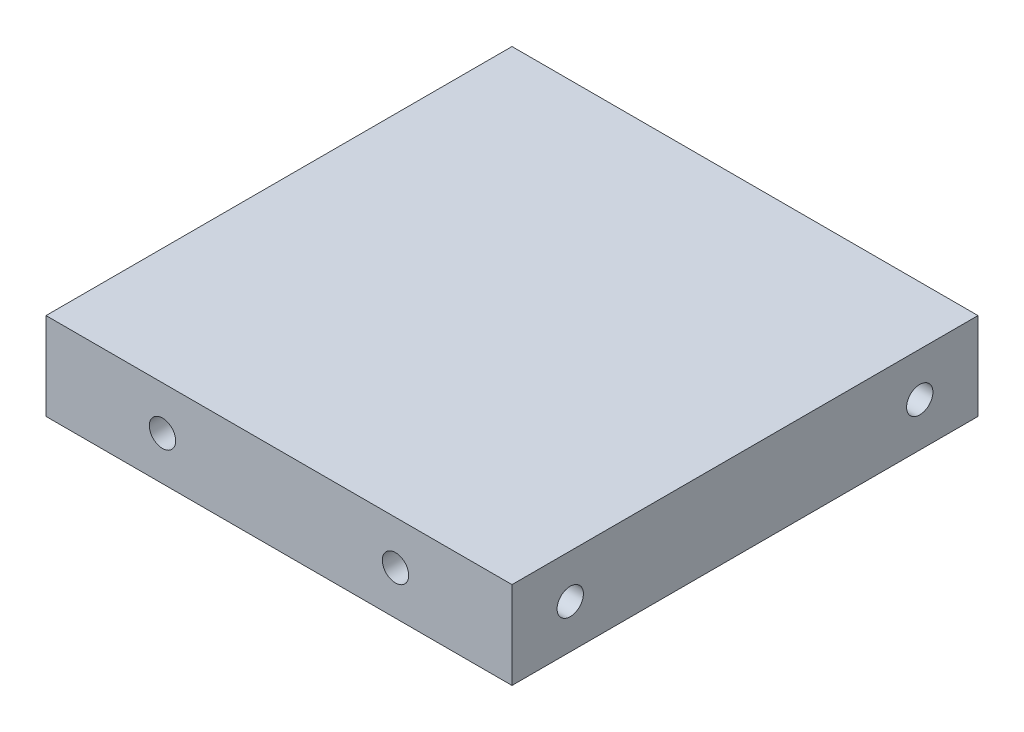
SolidWorks part; units mm, degrees
material "6061 Alloy"
ref_plane "Front Plane" through (0, 0, 0) normal (0, 0, 1) x (1, 0, 0)
ref_plane "Top Plane" through (0, 0, 0) normal (0, 1, 0) x (1, 0, 0)
ref_plane "Right Plane" through (0, 0, 0) normal (1, 0, 0) x (0, 0, -1)
sketch "Sketch1" plane through (0, 0, 0) normal (0, 1, 0) x (1, 0, 0)
  line L1 (20, -20) -> (-20, -20)
  line L2 (20, -20) -> (20, 20)
  line L3 (20, 20) -> (-20, 20)
  line L4 (-20, -20) -> (-20, 20)
  line L5 (20, -20) -> (-20, 20) construction
  line L6 (20, 20) -> (-20, -20) construction
  point P0 (0, 0)
  dimension "D1" = 40
  dimension "D2" = 40
extrude "Boss-Extrude1" add sketch "Sketch1" along normal blind 7.5
sketch "Sketch2" plane through (-20, 0, 0) normal (-1, 0, 0) x (0, 0, 1)
  line L0 (15, 3.75) -> (-15, 3.75)
  line L1 (-20, 0) -> (20, 0) construction
  point P3 (0, 3.75)
  dimension "D1" = 3.75
  dimension "D2" = 30
hole_wizard "#4-40 Tapped Hole1" positions "Sketch3" profile "Sketch4" tap size "#4-40" standard "ANSI Inch"
sketch "Sketch3" plane through (-20, 0, 0) normal (-1, 0, 0) x (0, 0, 1)
  point P0 (-15, 3.75)
  point P3 (15, 3.75)
sketch "Sketch4" plane through (-20, 3.75, -15) normal (0, 1, 0) x (0, 0, 1)
  line L0 (0, 0) -> (0, 8.2792)
  line L1 (0, 8.2792) -> (1.1303, 7.6)
  line L2 (1.1303, 7.6) -> (1.1303, 0)
  line L5 (1.1303, 0) -> (0, 0)
  line L10 (0, 8.2792) -> (-1.1303, 7.6) construction
  line L11 (0, -6.35) -> (0, 107.95) construction
  dimension "Tap Drill Dia." = 2.2606
  dimension "Tap Drill Depth" = 7.6
  dimension "Drill Angle" = 118
cosmetic thread "Hole Thread1" parameters "D1"=5.69, "D2"=2.8448
cosmetic thread "Hole Thread2" parameters "D1"=5.69, "D2"=2.8448
hole_wizard "#4-40 Tapped Hole2" positions "Sketch5" profile "Sketch6" tap size "#4-40" standard "ANSI Inch"
sketch "Sketch5" plane through (20, 0, 0) normal (1, 0, 0) x (0, 0, -1)
  point P0 (-15, 3.75)
  point P3 (15, 3.75)
sketch "Sketch6" plane through (20, 3.75, 15) normal (0, 1, 0) x (0, 0, -1)
  line L0 (0, 0) -> (0, 8.2792)
  line L1 (0, 8.2792) -> (1.1303, 7.6)
  line L2 (1.1303, 7.6) -> (1.1303, 0)
  line L5 (1.1303, 0) -> (0, 0)
  line L10 (0, 8.2792) -> (-1.1303, 7.6) construction
  line L11 (0, -6.35) -> (0, 107.95) construction
  dimension "Tap Drill Dia." = 2.2606
  dimension "Tap Drill Depth" = 7.6
  dimension "Drill Angle" = 118
cosmetic thread "Hole Thread3" parameters "D1"=5.69, "D2"=2.8448
cosmetic thread "Hole Thread4" parameters "D1"=5.69, "D2"=2.8448
sketch "Sketch7" plane through (0, 0, -20) normal (0, 0, -1) x (-1, 0, 0)
  line L0 (0, 0) -> (0, 7.5)
  line L1 (-20, 7.5) -> (20, 7.5) construction
  line L2 (10, 3.75) -> (-10, 3.75)
  point P8 (0, 3.75)
  dimension "D1" = 20
hole_wizard "#4-40 Tapped Hole3" positions "Sketch8" profile "Sketch9" tap size "#4-40" standard "ANSI Inch"
sketch "Sketch8" plane through (0, 0, -20) normal (0, 0, -1) x (-1, 0, 0)
  point P0 (-10, 3.75)
  point P3 (10, 3.75)
sketch "Sketch9" plane through (10, 3.75, -20) normal (1, 0, 0) x (0, 1, 0)
  line L0 (0, 0) -> (0, 8.2792)
  line L1 (0, 8.2792) -> (1.1303, 7.6)
  line L2 (1.1303, 7.6) -> (1.1303, 0)
  line L5 (1.1303, 0) -> (0, 0)
  line L10 (0, 8.2792) -> (-1.1303, 7.6) construction
  line L11 (0, -6.35) -> (0, 107.95) construction
  dimension "Tap Drill Dia." = 2.2606
  dimension "Tap Drill Depth" = 7.6
  dimension "Drill Angle" = 118
cosmetic thread "Hole Thread5" parameters "D1"=5.69, "D2"=2.8448
cosmetic thread "Hole Thread6" parameters "D1"=5.69, "D2"=2.8448
hole_wizard "#4-40 Tapped Hole4" positions "Sketch10" profile "Sketch11" tap size "#4-40" standard "ANSI Inch"
sketch "Sketch10" plane through (0, 0, 20) normal (0, 0, 1) x (1, 0, 0)
  point P0 (-10, 3.75)
  point P3 (10, 3.75)
sketch "Sketch11" plane through (-10, 3.75, 20) normal (1, 0, 0) x (0, -1, 0)
  line L0 (0, 0) -> (0, 8.2792)
  line L1 (0, 8.2792) -> (1.1303, 7.6)
  line L2 (1.1303, 7.6) -> (1.1303, 0)
  line L5 (1.1303, 0) -> (0, 0)
  line L10 (0, 8.2792) -> (-1.1303, 7.6) construction
  line L11 (0, -6.35) -> (0, 107.95) construction
  dimension "Tap Drill Dia." = 2.2606
  dimension "Tap Drill Depth" = 7.6
  dimension "Drill Angle" = 118
cosmetic thread "Hole Thread7" parameters "D1"=5.69, "D2"=2.8448
cosmetic thread "Hole Thread8" parameters "D1"=5.69, "D2"=2.8448
